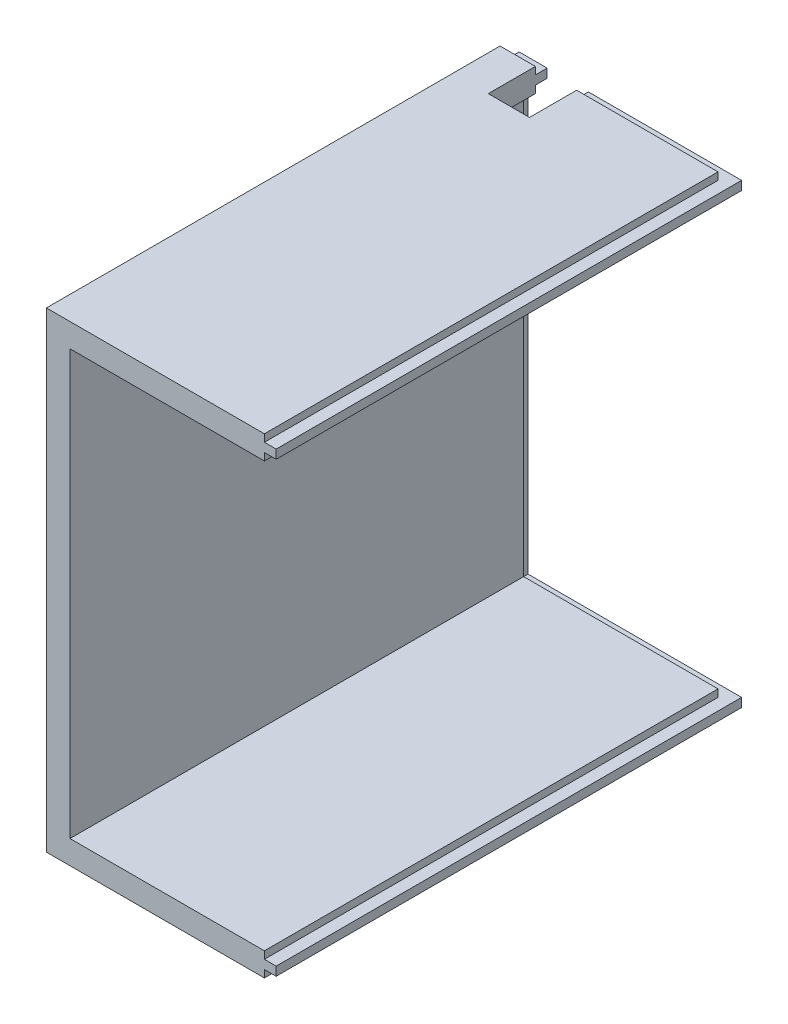
SolidWorks part; units mm, degrees
ref_plane "Ön Düzlem" through (0, 0, 0) normal (0, 0, 1) x (1, 0, 0)
ref_plane "Üst Düzlem" through (0, 0, 0) normal (0, 1, 0) x (1, 0, 0)
ref_plane "Sağ Düzlem" through (0, 0, 0) normal (1, 0, 0) x (0, 0, -1)
sketch "Çizim2" plane through (0, 0, 0) normal (0, 0, 1) x (1, 0, 0)
  line L1 (-19.5, 40) -> (19.5, 40)
  line L2 (-19.5, 40) -> (-19.5, -40)
  line L3 (-19.5, -40) -> (19.5, -40)
  line L4 (19.5, 40) -> (19.5, -40)
  line L5 (-19.5, 40) -> (19.5, -40) construction
  line L6 (-19.5, -40) -> (19.5, 40) construction
  line L7 (-15.5, 36) -> (19.5, 36)
  line L8 (-15.5, 36) -> (-15.5, -36)
  line L9 (-15.5, -36) -> (19.5, -36)
  line L10 (19.5, 36) -> (19.5, -36)
  line L11 (-15.5, 36) -> (19.5, -36) construction
  line L12 (-15.5, -36) -> (19.5, 36) construction
  point P0 (0, 0)
  point P6 (2, 0)
  dimension "D1" = 39
  dimension "D2" = 80
  dimension "D3" = 4
  dimension "D4" = 35
  dimension "D5" = 72
  dimension "D6" = 4
extrude "Yükseklik-Ekstrüzyon2" add sketch "Çizim2" against normal blind 77 contours L9 L8 L7 L4 L1 L2 L3
sketch "Çizim3" plane through (0, 0, -77) normal (0, 0, -1) x (-1, 0, 0)
  line L0 (15.5, -36) -> (-19.5, -36) construction
  line L1 (-19.5, -36) -> (-17.5, -36)
  line L2 (-19.5, -36) -> (-19.5, -37.25)
  line L3 (-19.5, -37.25) -> (-17.5, -37.25)
  line L4 (-17.5, -36) -> (-17.5, -37.25)
  line L5 (-19.5, -36) -> (-17.5, -37.25) construction
  line L6 (-19.5, -37.25) -> (-17.5, -36) construction
  line L7 (-19.5, -36) -> (-19.5, -40) construction
  line L8 (-19.5, -38.75) -> (-17.5, -38.75)
  line L9 (-19.5, -38.75) -> (-19.5, -40)
  line L10 (-19.5, -40) -> (-17.5, -40)
  line L11 (-17.5, -38.75) -> (-17.5, -40)
  line L12 (-19.5, -38.75) -> (-17.5, -40) construction
  line L13 (-19.5, -40) -> (-17.5, -38.75) construction
  line L14 (19.5, -40) -> (-19.5, -40) construction
  line L15 (-19.5, 40) -> (-17.5, 40)
  line L16 (-19.5, 40) -> (-19.5, 38.75)
  line L17 (-19.5, 38.75) -> (-17.5, 38.75)
  line L18 (-17.5, 40) -> (-17.5, 38.75)
  line L19 (-19.5, 40) -> (-17.5, 38.75) construction
  line L20 (-19.5, 38.75) -> (-17.5, 40) construction
  line L21 (-19.5, 37.25) -> (-17.5, 37.25)
  line L22 (-19.5, 37.25) -> (-19.5, 36)
  line L23 (-19.5, 36) -> (-17.5, 36)
  line L24 (-17.5, 37.25) -> (-17.5, 36)
  line L25 (-19.5, 37.25) -> (-17.5, 36) construction
  line L26 (-19.5, 36) -> (-17.5, 37.25) construction
  line L27 (19.5, 40) -> (-19.5, 40) construction
  line L28 (-19.5, 40) -> (-19.5, 36) construction
  line L29 (15.5, 36) -> (-19.5, 36) construction
  point P0 (-18.5, -36.625)
  point P9 (-18.5, -39.375)
  point P16 (-18.5, 39.375)
  point P21 (-18.5, 36.625)
  dimension "D1" = 2
  dimension "D2" = 1.25
  dimension "D3" = 0
  dimension "D4" = 0
  dimension "D5" = 2
  dimension "D6" = 1.25
  dimension "D7" = 0
  dimension "D8" = 0
  dimension "D9" = 2
  dimension "D10" = 1.25
  dimension "D11" = 2
  dimension "D12" = 1.25
  dimension "D13" = 0
  dimension "D14" = 0
  dimension "D15" = 0
  dimension "D16" = 0
extrude "Kes-Ekstrüzyon1" cut sketch "Çizim3" against normal blind 77
sketch "Çizim6" plane through (0, 0, -77) normal (0, 0, -1) x (-1, 0, 0)
  line L0 (19.5, 40) -> (19.5, -40) construction
  line L1 (-91.5, 38.75) -> (18.25, 38.75)
  line L2 (-91.5, 38.75) -> (-91.5, 37.25)
  line L3 (-91.5, 37.25) -> (18.25, 37.25)
  line L4 (18.25, 38.75) -> (18.25, 37.25)
  line L5 (-91.5, 38.75) -> (18.25, 37.25) construction
  line L6 (-91.5, 37.25) -> (18.25, 38.75) construction
  line L7 (19.5, 40) -> (-17.5, 40) construction
  line L8 (-91.5, -37.25) -> (18.25, -37.25)
  line L9 (-91.5, -37.25) -> (-91.5, -38.75)
  line L10 (-91.5, -38.75) -> (18.25, -38.75)
  line L11 (18.25, -37.25) -> (18.25, -38.75)
  line L12 (-91.5, -37.25) -> (18.25, -38.75) construction
  line L13 (-91.5, -38.75) -> (18.25, -37.25) construction
  line L14 (15.5, -36) -> (-17.5, -36) construction
  line L16 (16.75, 37.25) -> (18.25, 37.25)
  line L17 (16.75, 37.25) -> (16.75, -37.25)
  line L18 (16.75, -37.25) -> (18.25, -37.25)
  line L19 (18.25, 37.25) -> (18.25, -37.25)
  line L20 (16.75, 37.25) -> (18.25, -37.25) construction
  line L21 (16.75, -37.25) -> (18.25, 37.25) construction
  point P0 (-36.625, 38)
  point P9 (-36.625, -38)
  point P16 (17.5, 0)
  line M19 (-17.5, 38.75) -> (-19.5, 38.75)
  line M20 (-19.5, 38.75) -> (-19.5, 37.25)
  line M21 (-19.5, 37.25) -> (-17.5, 37.25)
  line M27 (-17.5, -37.25) -> (-19.5, -37.25)
  line M28 (-19.5, -37.25) -> (-19.5, -38.75)
  line M29 (-19.5, -38.75) -> (-17.5, -38.75)
  dimension "D1" = 1.5
  dimension "D2" = 1.25
  dimension "D3" = 1.25
  dimension "D4" = 109.75
  dimension "D5" = 1.5
  dimension "D6" = 109.75
  dimension "D7" = 1.25
  dimension "D8" = 1.25
  dimension "D9" = 1.5
  dimension "D10" = 1.25
  dimension "D11" = 0
  dimension "D12" = 0
extrude "Yükseklik-Ekstrüzyon3" add sketch "Çizim6" along normal blind 2 contours L4 L1 L3 M19 M20 M21 | L19 L3 L17 L8 | L11 L8 L10 M27 M28 M29
sketch "Çizim7" plane through (0, 40, 0) normal (0, 1, 0) x (1, 0, 0)
  line L0 (17.5, 77) -> (-18.25, 77) construction
  line L1 (-13.5, 79) -> (-6.5, 79)
  line L2 (-13.5, 79) -> (-13.5, 69)
  line L3 (-13.5, 69) -> (-6.5, 69)
  line L4 (-6.5, 79) -> (-6.5, 69)
  line L5 (-13.5, 79) -> (-6.5, 69) construction
  line L6 (-13.5, 69) -> (-6.5, 79) construction
  line L7 (-19.5, 77) -> (-19.5, 0) construction
  point P0 (-10, 74)
  dimension "D1" = 7
  dimension "D2" = 10
  dimension "D3" = 8
  dimension "D4" = 6
extrude "Kes-Ekstrüzyon2" cut sketch "Çizim7" against normal blind 5
